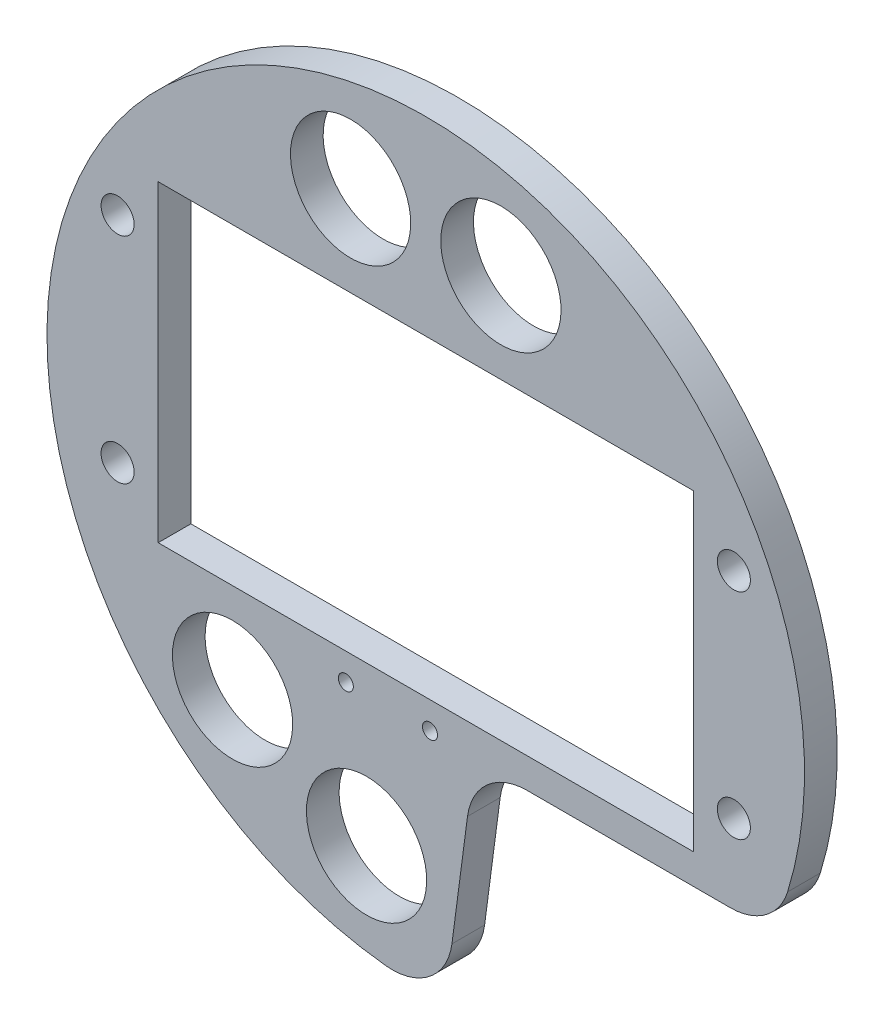
SolidWorks part; units mm, degrees
material "Acrylic (Medium-high impact)"
ref_plane "Front Plane" through (0, 0, 0) normal (0, 0, 1) x (1, 0, 0)
ref_plane "Top Plane" through (0, 0, 0) normal (0, 1, 0) x (1, 0, 0)
ref_plane "Right Plane" through (0, 0, 0) normal (1, 0, 0) x (0, 0, -1)
ref_plane "Plane1" through (0, 0, -110.625) normal (0, 0, -1) x (-1, 0, 0)
sketch "Sketch2" plane through (0, 0, -110.625) normal (0, 0, -1) x (-1, 0, 0)
  line L0 (0, 63) -> (0, -63) construction
  line L1 (44.5, 5.3438) -> (-44.5, 5.3438) construction
  line L2 (44.5, -20.6562) -> (-44.5, -20.6562)
  line L3 (44.5, -20.6562) -> (44.5, 31.3438)
  line L4 (44.5, 31.3438) -> (-44.5, 31.3438)
  line L5 (-44.5, -20.6562) -> (-44.5, 31.3438)
  line L6 (44.5, -20.6562) -> (-44.5, 31.3438) construction
  line L7 (44.5, 31.3438) -> (-44.5, -20.6562) construction
  line L8 (12.5, 46.3438) -> (-12.5, 46.3438) construction
  line L9 (-4.3574, -54.0131) -> (-6.946, -34.3509)
  line L10 (-16.8605, -25.6562) -> (-50.6348, -25.6562)
  line L11 (51.25, 23.184) -> (51.25, -12.4964) construction
  line L12 (-51.25, 23.184) -> (-51.25, -12.4964) construction
  line L13 (-51.25, -12.4964) -> (51.25, -12.4964) construction
  line L14 (51.25, 23.184) -> (-51.25, 23.184) construction
  line L15 (13.2914, -25.1562) -> (-0.7086, -25.1562) construction
  line L16 (17.2914, -22.1562) -> (-4.7086, -22.1562) construction
  line L17 (17.7914, -22.6562) -> (17.7914, -36.0562) construction
  line L18 (17.7914, -36.0562) -> (-5.2086, -36.0562) construction
  line L19 (-5.2086, -22.6562) -> (-5.2086, -36.0562) construction
  line L20 (6.2914, -22.1562) -> (6.2914, -36.0562) construction
  circle A0 centre (0, 0) radius 63.5 construction
  arc A1 (6.6055, -62.6528) -> (-60.1885, -18.6102) centre (0, 0) ccw
  circle A2 centre (12.5, 46.3438) radius 15 construction
  circle A3 centre (12.5, 46.3438) radius 10
  circle A4 centre (-12.5, 46.3438) radius 10
  circle A5 centre (32.1347, -35.6562) radius 10
  circle A6 centre (32.1347, -35.6562) radius 15 construction
  circle A7 centre (9.846, -46.9793) radius 10
  circle A8 centre (9.846, -46.9793) radius 15 construction
  arc A9 (-57.5392, -25.6562) -> (-3.1849, -62.9194) centre (0, 0) ccw construction
  arc A10 (-50.6348, -25.6562) -> (-60.1885, -18.6102) centre (-50.6348, -15.6562) cw
  arc A11 (-6.946, -34.3509) -> (-16.8605, -25.6562) centre (-16.8605, -35.6562) ccw
  arc A12 (-4.3574, -54.0131) -> (6.6055, -62.6528) centre (5.557, -52.7079) ccw
  circle A13 centre (51.25, 23.184) radius 2.75
  circle A14 centre (51.25, -12.4964) radius 2.75
  circle A15 centre (-51.25, -12.4964) radius 2.75
  circle A16 centre (-51.25, 23.184) radius 2.75
  circle A17 centre (51.25, 23.184) radius 6.75 construction
  circle A18 centre (13.2914, -25.1562) radius 1.25
  circle A19 centre (-0.7086, -25.1562) radius 1.25
  arc A20 (-4.7086, -22.1562) -> (-5.2086, -22.6562) centre (-4.7086, -22.6562) ccw construction
  arc A21 (17.2914, -22.1562) -> (17.7914, -22.6562) centre (17.2914, -22.6562) cw construction
  point P0 (0, 0)
  point P8 (0, 5.3438)
  point P40 (0, 23.184)
  point P42 (51.25, 5.3438)
  point P57 (6.2914, -25.1562)
  point P60 (-5.2086, -22.1562)
  point P63 (17.7914, -22.1562)
  dimension "D1" = 127
  dimension "D2" = 0.5
  dimension "D5" = 5
  dimension "D6" = 20
  dimension "D9" = 10
  dimension "D10" = 5.5
  dimension "D11" = 4
  dimension "D14" = 2.5
  dimension "D17" = 0.5
  dimension "D3" = 89
  dimension "D4" = 52
  dimension "D7" = 5
  dimension "D8" = 7.5
  dimension "D12" = 23
  dimension "D13" = 13.9
  dimension "D15" = 3
  dimension "D16" = 14
  dimension "D18" = 1.5
  dimension "D19" = 1.5
extrude "Boss-Extrude1" add sketch "Sketch2" against normal blind 5.4356
